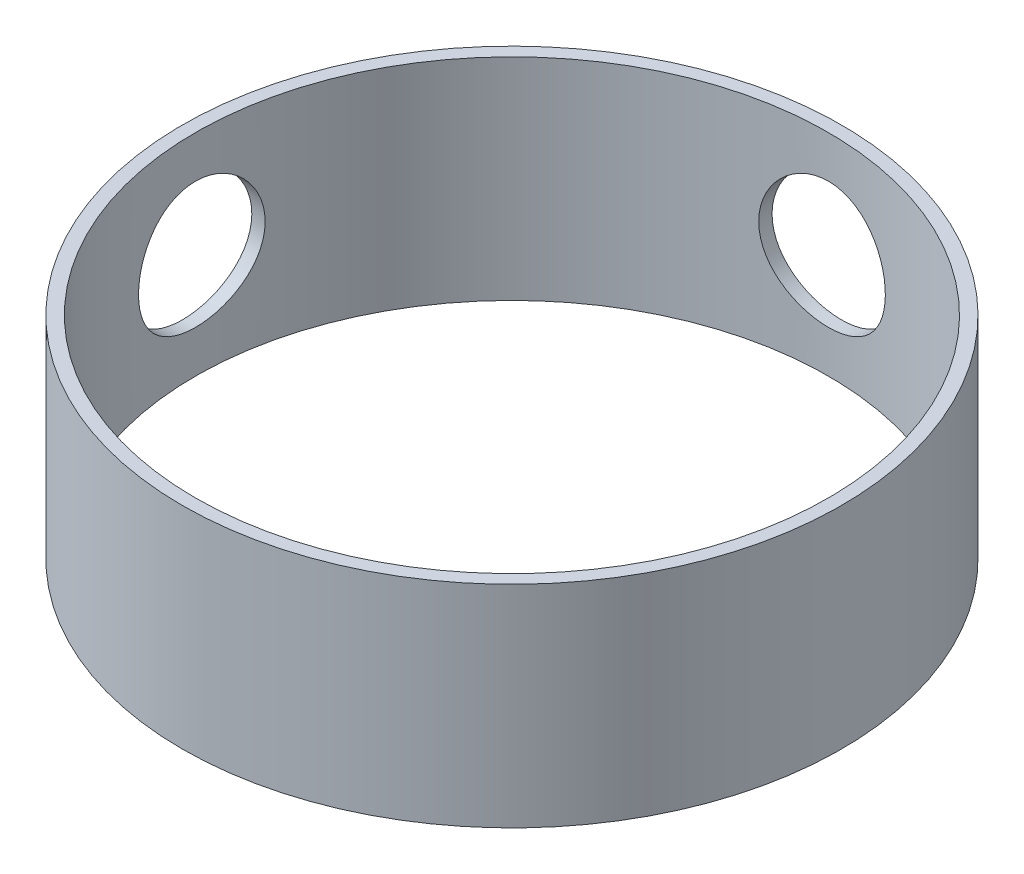
SolidWorks part; units mm, degrees
ref_plane "Front Plane" through (0, 0, 0) normal (0, 0, 1) x (1, 0, 0)
ref_plane "Top Plane" through (0, 0, 0) normal (0, 1, 0) x (1, 0, 0)
ref_plane "Right Plane" through (0, 0, 0) normal (1, 0, 0) x (0, 0, -1)
sketch "Sketch1" plane through (0, 0, 0) normal (0, 1, 0) x (1, 0, 0)
  circle A0 centre (0, 0) radius 38.1
  circle A1 centre (0, 0) radius 39.6748
  dimension "D1" = 76.2
  dimension "D2" = 79.3496
extrude "Boss-Extrude1" add sketch "Sketch1" along normal mid plane 25.4
sketch "Sketch2" plane through (0, 0, 0) normal (0, 0, 1) x (1, 0, 0)
  circle A0 centre (0, 0) radius 7.62
  dimension "D1" = 15.24
extrude "Cut-Extrude1" cut sketch "Sketch2" against normal through all
sketch "Sketch3" plane through (0, 0, 0) normal (1, 0, 0) x (0, 0, -1)
  circle A0 centre (0, 0) radius 7.62
  dimension "D1" = 15.24
extrude "Cut-Extrude2" cut sketch "Sketch3" against normal through all
equation "\"airframeInnerDiameter\"=3"
equation "\"outerDiameter\"=3.124"
equation "\"recoveryBandLength\"=1"
equation "\"D1@Sketch1\"=\"airframeInnerDiameter\""
equation "\"D2@Sketch1\"=\"outerDiameter\""
equation "\"D1@Boss-Extrude1\"=\"recoveryBandLength\""
